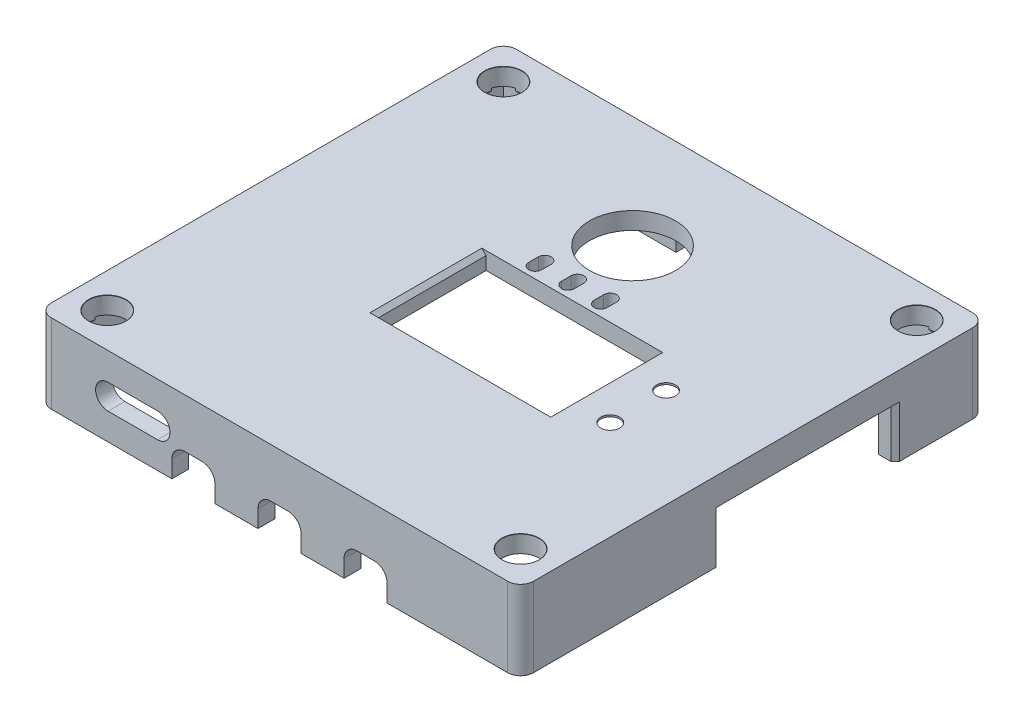
SolidWorks part; units mm, degrees
ref_plane "前视基准面" through (0, 0, 0) normal (0, 0, 1) x (1, 0, 0)
ref_plane "上视基准面" through (0, 0, 0) normal (0, 1, 0) x (1, 0, 0)
ref_plane "右视基准面" through (0, 0, 0) normal (1, 0, 0) x (0, 0, -1)
other "Configuration Table"
sketch "草图1" plane through (0, 0, 0) normal (0, 1, 0) x (1, 0, 0)
  line L1 (-28, 27) -> (28, 27)
  line L2 (-28, 27) -> (-28, -27)
  line L3 (-28, -27) -> (28, -27)
  line L4 (28, 27) -> (28, -27)
  line L5 (-28, 27) -> (28, -27) construction
  line L6 (-28, -27) -> (28, 27) construction
  line L9 (0, 27) -> (0, 14) construction
  line L15 (-10.3562, 9.9863) -> (10.3562, -9.9863) construction
  line L16 (-10.3562, -9.9863) -> (10.3562, 9.9863) construction
  circle A0 centre (0, 14) radius 5
  point P0 (0, 0)
  point P9 (0, 0)
  point P14 (0, 0)
  dimension "D4" = 10
  dimension "D1" = 56
  dimension "D2" = 54
  dimension "D3" = 13
extrude "凸台-拉伸1" add sketch "草图1" along normal blind 9.2
hole_wizard "M2 六角圆柱头螺钉的柱形沉头孔1" positions "草图7" profile "草图6" counterbore size "M2" standard "GB" end condition through all
sketch "草图7" plane through (0, 9.2, 0) normal (0, 1, 0) x (1, 0, 0)
  line L0 (-28, 27) -> (-28, -27) construction
  line L1 (-28, -27) -> (28, -27) construction
  line L2 (28, -27) -> (28, 27) construction
  line L3 (28, 27) -> (-28, 27) construction
  point P14 (-24, 23)
  point P16 (24, 23)
  point P18 (-24, -23)
  point P20 (24, -23)
  dimension "D1" = 4
  dimension "D2" = 4
  dimension "D3" = 4
  dimension "D4" = 4
  dimension "D5" = 4
  dimension "D6" = 4
  dimension "D7" = 4
  dimension "D8" = 4
sketch "草图6" plane through (-24, 9.2, -23) normal (1, 0, 0) x (0, 0, 1)
  line L0 (0, 0) -> (0, 9.2)
  line L1 (0, 9.2) -> (1.3, 9.2)
  line L3 (1.3, 9.2) -> (1.3, 2.3)
  line L4 (2.15, 2.3) -> (1.3, 2.3)
  line L5 (2.15, 2.3) -> (2.15, 0.025)
  line L6 (2.15, 0.025) -> (2.175, 0)
  line L7 (2.175, 0) -> (0, 0)
  line L8 (-2.15, 0.025) -> (-2.175, 0) construction
  line L11 (0, -6.35) -> (0, 107.95) construction
  dimension "通孔孔直径" = 2.6
  dimension "通孔孔深度" = 9.2
  dimension "柱形沉头孔直径" = 4.3
  dimension "柱形沉头孔深度" = 2.3
  dimension "近端锥形沉头孔直径" = 4.35
  dimension "近端锥形沉头孔角度" = 90
ref_plane "控制板上表面" through (0, 7.2, 0) normal (0, 1, 0) x (1, 0, 0)
sketch "草图13" plane through (0, 7.2, 0) normal (0, 1, 0) x (1, 0, 0)
  line L1 (-26.05, 25.05) -> (26.05, 25.05)
  line L2 (-26.05, 25.05) -> (-26.05, -25.05)
  line L3 (-26.05, -25.05) -> (26.05, -25.05)
  line L4 (26.05, 25.05) -> (26.05, -25.05)
  line L5 (-26.05, 25.05) -> (26.05, -25.05) construction
  line L6 (-26.05, -25.05) -> (26.05, 25.05) construction
  point P0 (0, 0)
  dimension "D1" = 52.1
  dimension "D2" = 50.1
extrude "切除-拉伸1" cut sketch "草图13" against normal through all
sketch "草图14" plane through (0, 9.2, 0) normal (0, 1, 0) x (1, 0, 0)
  line L1 (-8, 5) -> (12, 5)
  line L2 (-8, 5) -> (-8, -8)
  line L3 (-8, -8) -> (12, -8)
  line L4 (12, 5) -> (12, -8)
  line L5 (-28, -27) -> (28, -27) construction
  line L6 (28, -27) -> (28, 27) construction
  dimension "D1" = 16
  dimension "D2" = 19
  dimension "D3" = 20
  dimension "D4" = 13
extrude "切除-拉伸2" cut sketch "草图14" against normal through all
sketch "草图15" plane through (0, 9.2, 0) normal (0, 1, 0) x (1, 0, 0)
  line L0 (12, -8) -> (12, 5) construction
  circle A0 centre (16.5, 1.39) radius 1.1
  circle A1 centre (16.5, -5.09) radius 1.1
  dimension "D1" = 2.2
  dimension "D2" = 2.2
  dimension "D3" = 6.48
  dimension "D4" = 4.5
  dimension "D5" = 3.61
extrude "切除-拉伸4" cut sketch "草图15" against normal through all
sketch "草图18" plane through (0, 0, -27) normal (0, 0, -1) x (-1, 0, 0)
  line L0 (-28, 0) -> (28, 0) construction
  line L1 (0, 0) -> (0, 9.2) construction
  line L2 (-6, 5) -> (-1, 5)
  line L3 (-6, 5) -> (-6, 0)
  line L4 (-6, 0) -> (-1, 0)
  line L5 (-1, 5) -> (-1, 0)
  line L6 (-28, 9.2) -> (28, 9.2) construction
  line L7 (1, 5) -> (6, 5)
  line L8 (1, 5) -> (1, 0)
  line L9 (1, 0) -> (6, 0)
  line L10 (6, 5) -> (6, 0)
  point P15 (-3.5, 5)
  point P16 (3.5, 5)
  dimension "D1" = 5
  dimension "D2" = 5
  dimension "D3" = 7
extrude "切除-拉伸7" cut sketch "草图18" against normal up to next
ref_plane "基准面4" through (0, 6, 0) normal (0, 1, 0) x (1, 0, 0)
sketch "草图20" plane through (-28, 0, 0) normal (-1, 0, 0) x (0, 0, 1)
  line L0 (-27, 0) -> (27, 0) construction
  line L1 (29.7, 6) -> (-29.7, 6) construction
  line L2 (3.8, 0) -> (-14, 0)
  line L3 (3.8, 0) -> (3.8, 6)
  line L4 (3.8, 6) -> (-14, 6)
  line L5 (-14, 0) -> (-14, 6)
  line L6 (-27, 9.2) -> (-27, 0) construction
  dimension "D1" = 17.8
  dimension "D2" = 13
extrude "切除-拉伸8" cut sketch "草图20" against normal up to next
sketch "草图23" plane through (28, 0, 0) normal (1, 0, 0) x (0, 0, -1)
  line L0 (-27, 0) -> (27, 0) construction
  line L1 (-3.83, 0) -> (16.49, 0)
  line L2 (-3.83, 0) -> (-3.83, 6)
  line L3 (-3.83, 6) -> (16.49, 6)
  line L4 (16.49, 0) -> (16.49, 6)
  line L5 (-3.8, 6) -> (14, 6) construction
  line L7 (27, 9.2) -> (27, 0) construction
  dimension "D1" = 20.32
  dimension "D2" = 10.51
extrude "切除-拉伸9" cut sketch "草图23" against normal up to next
chamfer "倒角1" distance 0.5 angle 45 2 edges at (12, 9.2, 1.5) (-8, 9.2, 1.5)
sketch "草图24" plane through (0, 0, 27) normal (0, 0, 1) x (1, 0, 0)
  line L0 (-19.91, 4.55) -> (-14.17, 4.55) construction
  line L1 (-19.91, 6) -> (-14.17, 6)
  line L2 (-19.91, 3.1) -> (-14.17, 3.1)
  line L3 (-28, 0) -> (-28, 6) construction
  line L4 (-28, 9.2) -> (28, 9.2) construction
  arc A0 (-19.91, 6) -> (-19.91, 3.1) centre (-19.91, 4.55) ccw
  arc A1 (-14.17, 3.1) -> (-14.17, 6) centre (-14.17, 4.55) ccw
  point P2 (-17.04, 4.55)
  point P7 (-21.36, 4.55)
  point P12 (-12.72, 4.55)
  dimension "D1" = 6.64
  dimension "D2" = 3.2
  dimension "D3" = 8.64
  dimension "D4" = 2.9
extrude "切除-拉伸10" cut sketch "草图24" against normal up to next
fillet "圆角4" radius 1.5 4 edges at (-6, 5, -26.025) (-1, 5, -26.025) (1, 5, -26.025) (6, 5, -26.025)
chamfer "倒角2" distance 0.5 angle 45 2 edges at (28, 3, -16.49) (28, 3, 3.83)
chamfer "倒角3" distance 0.5 angle 45 2 edges at (-28, 3, 3.8) (-28, 3, -14)
sketch "草图25" plane through (0, 0, 27) normal (0, 0, 1) x (1, 0, 0)
  line L0 (-28, 0) -> (28, 0) construction
  line L1 (-12.5, 0) -> (-7.5, 0)
  line L2 (-12.5, 0) -> (-12.5, 3.5)
  line L3 (-12.5, 3.5) -> (-7.5, 3.5)
  line L4 (-7.5, 0) -> (-7.5, 3.5)
  line L5 (-28, 0) -> (-28, 6) construction
  line L6 (0, 0) -> (0, 9.2) construction
  line L7 (-28, 9.2) -> (28, 9.2) construction
  line L8 (12.5, 3.5) -> (7.5, 3.5)
  line L9 (7.5, 0) -> (7.5, 3.5)
  line L10 (12.5, 0) -> (7.5, 0)
  line L11 (12.5, 0) -> (12.5, 3.5)
  line L13 (-2.5, 3.5) -> (2.5, 3.5)
  line L14 (-2.5, 3.5) -> (-2.5, 0)
  line L15 (-2.5, 0) -> (2.5, 0)
  line L16 (2.5, 3.5) -> (2.5, 0)
  point P6 (-10, 3.5)
  point P22 (0, 0)
  dimension "D1" = 18
  dimension "D2" = 3.5
  dimension "D3" = 5
  dimension "D4" = 3.5
  dimension "D5" = 5
extrude "切除-拉伸11" cut sketch "草图25" against normal up to next
fillet "圆角5" radius 1.5 6 edges at (12.5, 3.5, 26.025) (7.5, 3.5, 26.025) (2.5, 3.5, 26.025) (-2.5, 3.5, 26.025) (-7.5, 3.5, 26.025) (-12.5, 3.5, 26.025)
sketch "草图30" plane through (0, 0, -27) normal (0, 0, -1) x (-1, 0, 0)
  line L0 (29.7, 6) -> (-29.7, 6) construction
  line L1 (-17.25, 6) -> (-10.75, 6)
  line L2 (-17.25, 6) -> (-17.25, 1.2)
  line L3 (-17.25, 1.2) -> (-10.75, 1.2)
  line L4 (-10.75, 6) -> (-10.75, 1.2)
  line L5 (-28, 9.2) -> (-28, 0) construction
  line L6 (6, 0) -> (28, 0) construction
  line L7 (12.3, 6) -> (20.3, 6)
  line L8 (12.3, 6) -> (12.3, 0)
  line L9 (12.3, 0) -> (20.3, 0)
  line L10 (20.3, 6) -> (20.3, 0)
  line L11 (28, 0) -> (28, 6) construction
  point P6 (-14, 1.2)
  point P15 (16.3, 0)
  dimension "D1" = 14
  dimension "D2" = 6.5
  dimension "D3" = 4.8
  dimension "D4" = 11.7
  dimension "D5" = 8
extrude "切除-拉伸12" cut sketch "草图30" against normal up to next
sketch "草图33" plane through (0, 9.2, 0) normal (0, 1, 0) x (1, 0, 0)
  line L0 (-3.6, 7.4) -> (-3.6, 6.3) construction
  line L1 (-2.85, 7.4) -> (-2.85, 6.3)
  line L2 (-4.35, 7.4) -> (-4.35, 6.3)
  line L3 (0.2, 7.4) -> (0.2, 6.3) construction
  line L4 (0.95, 7.4) -> (0.95, 6.3)
  line L5 (-0.55, 7.4) -> (-0.55, 6.3)
  line L6 (4, 7.4) -> (4, 6.3) construction
  line L7 (4.75, 7.4) -> (4.75, 6.3)
  line L8 (3.25, 7.4) -> (3.25, 6.3)
  line L10 (12, -8) -> (12, 5) construction
  line L11 (12.5, 5) -> (-8.5, 5) construction
  arc A0 (-2.85, 7.4) -> (-4.35, 7.4) centre (-3.6, 7.4) ccw
  arc A1 (-4.35, 6.3) -> (-2.85, 6.3) centre (-3.6, 6.3) ccw
  arc A2 (0.95, 7.4) -> (-0.55, 7.4) centre (0.2, 7.4) ccw
  arc A3 (-0.55, 6.3) -> (0.95, 6.3) centre (0.2, 6.3) ccw
  arc A4 (4.75, 7.4) -> (3.25, 7.4) centre (4, 7.4) ccw
  arc A5 (3.25, 6.3) -> (4.75, 6.3) centre (4, 6.3) ccw
  point P2 (-3.6, 6.85)
  point P7 (0.2, 6.85)
  point P14 (4, 6.85)
  point P21 (-3.6, 8.15)
  point P22 (-3.6, 5.55)
  dimension "D1" = 0.75
  dimension "D2" = 2.6
  dimension "D3" = 1.85
  dimension "D4" = 8
  dimension "D5" = 3.8
  dimension "D6" = 3.8
extrude "切除-拉伸13" cut sketch "草图33" against normal up to next
chamfer "倒角4" distance 0.5 angle 45 2 edges at (-20.3, 3, -27) (-12.3, 3, -27)
sketch "草图35" plane through (0, 7.2, 0) normal (0, -1, 0) x (1, 0, 0)
  line L0 (-28, 27) -> (-12.5, 27) construction
  line L1 (12.644, 8) -> (20.6186, 8)
  line L2 (12.644, 8) -> (12.644, -5)
  line L3 (12.644, -5) -> (20.6186, -5)
  line L4 (20.6186, 8) -> (20.6186, -5)
  line L5 (-7.5, 27) -> (-2.5, 27) construction
  line L6 (-10, 18.5) -> (-1, 18.5)
  line L7 (12, -5) -> (-8, -5) construction
  line L8 (-8, 8) -> (12, 8) construction
  line L9 (-28, 4.3) -> (-28, 27) construction
  line L10 (-22.2, 23.8) -> (-11.2, 23.8)
  line L11 (-22.2, 23.8) -> (-22.2, 17)
  line L12 (-22.2, 17) -> (-11.2, 17)
  line L13 (-11.2, 23.8) -> (-11.2, 17)
  line L14 (-10, 18.5) -> (-10, 8)
  line L15 (-10, 8) -> (-1, 8)
  line L16 (-1, 18.5) -> (-1, 8)
  line L17 (-28, -27) -> (-28, -14.5) construction
  line L18 (-18.05, -14.55) -> (-14.55, -14.55)
  line L19 (-18.05, -14.55) -> (-18.05, -16.05)
  line L20 (-18.05, -16.05) -> (-14.55, -16.05)
  line L21 (-14.55, -14.55) -> (-14.55, -16.05)
  line L22 (-20.8, -27) -> (-11.8, -27) construction
  point P10 (-16.7, 23.8)
  point P17 (-22.2, 20.4)
  point P30 (-16.3, -14.55)
  point P33 (-14.55, -15.3)
  point P34 (0, 0)
  point P35 (0, 0)
  dimension "D1" = 11
  dimension "D2" = 6.8
  dimension "D3" = 11.3
  dimension "D4" = 6.6
  dimension "D5" = 18
  dimension "D6" = 8.5
  dimension "D7" = 9
  dimension "D8" = 1.5
  dimension "D9" = 3.5
  dimension "D10" = 11.7
  dimension "D11" = 11.7
extrude "切除-拉伸14" cut sketch "草图35" against normal blind 1.8
fillet "圆角6" radius 1.5 4 edges at (-28, 4.6, -27) (28, 4.6, -27) (28, 4.6, 27) (-28, 4.6, 27)
